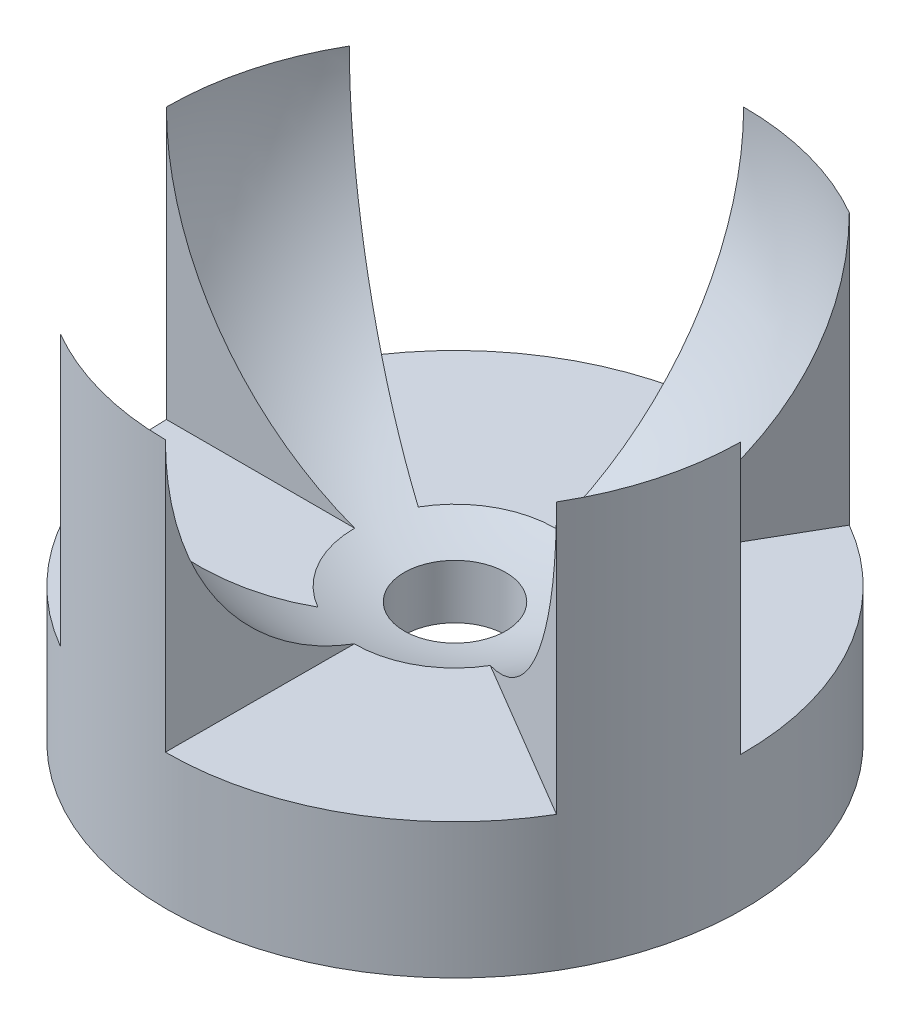
SolidWorks part; units mm, degrees
ref_plane "Front Plane" through (0, 0, 0) normal (0, 0, 1) x (1, 0, 0)
ref_plane "Top Plane" through (0, 0, 0) normal (0, 1, 0) x (1, 0, 0)
ref_plane "Right Plane" through (0, 0, 0) normal (1, 0, 0) x (0, 0, -1)
sketch "Sketch1" plane through (0, 0, 0) normal (0, 1, 0) x (1, 0, 0)
  circle A1 centre (0, 0) radius 85.3247
extrude "Boss-Extrude1" add sketch "Sketch1" along normal blind 40
sketch "Sketch2" plane through (0, 40, 0) normal (0, 1, 0) x (1, 0, 0)
  line L0 (-42.9157, -73.7466) -> (-5.0297, -8.643)
  line L1 (-0.2928, -85.3242) -> (-0.0343, -9.9999)
  line L2 (73.4438, -43.4317) -> (8.6076, -5.0902)
  line L3 (10, 0) -> (85.3201, -0.8911)
  line L4 (0, 10) -> (0, 85.3247)
  line L5 (5, 8.6603) -> (42.6624, 73.8934)
  line L6 (-10, 0) -> (-85.3247, 0)
  line L7 (-73.8934, 42.6624) -> (-8.6603, 5)
  arc A0 (-85.3247, 0) -> (-73.8934, 42.6624) centre (0, 0) cw
  circle A1 centre (0, 0) radius 85.3247 construction
  arc A2 (0, 85.3247) -> (42.6624, 73.8934) centre (0, 0) cw
  arc A3 (85.3201, -0.8911) -> (73.4438, -43.4317) centre (0, 0) cw
  arc A4 (-0.2928, -85.3242) -> (-42.9157, -73.7466) centre (0, 0) cw
  arc A5 (-10, 0) -> (-8.6603, 5) centre (0, 0) cw
  arc A6 (0, 10) -> (5, 8.6603) centre (0, 0) cw
  arc A7 (10, 0) -> (8.6076, -5.0902) centre (0, 0) cw
  arc A8 (-0.0343, -9.9999) -> (-5.0297, -8.643) centre (0, 0) cw
  circle M1 centre (0, 0) radius 85.3247
extrude "Boss-Extrude6" add sketch "Sketch2" along normal blind 80 contours L3 A7 L2 M1 | L1 A8 L0 M1 | L6 A0 L7 A5 | L4 A2 L5 A6
sketch "Sketch6" plane through (0, 0, 0) normal (0.866, 0, 0.5) x (0.5, 0, -0.866)
  line L0 (85.3247, 120) -> (0, 120)
  line L1 (0, 120) -> (0, 34.6753)
  arc A0 (85.3247, 120) -> (0, 34.6753) centre (0, 120) cw
revolve "Cut-Revolve1" cut sketch "Sketch6" angle 360 about L1
sketch "Sketch7" plane through (0, 0, 0) normal (0, -1, 0) x (1, 0, 0)
  circle A0 centre (0, 0) radius 50
extrude "Cut-Extrude1" cut sketch "Sketch7" against normal blind 20
sketch "Sketch8" plane through (0, 20, 0) normal (0, -1, 0) x (1, 0, 0)
  circle A0 centre (0, 0) radius 15
extrude "Cut-Extrude2" cut sketch "Sketch8" against normal blind 60
